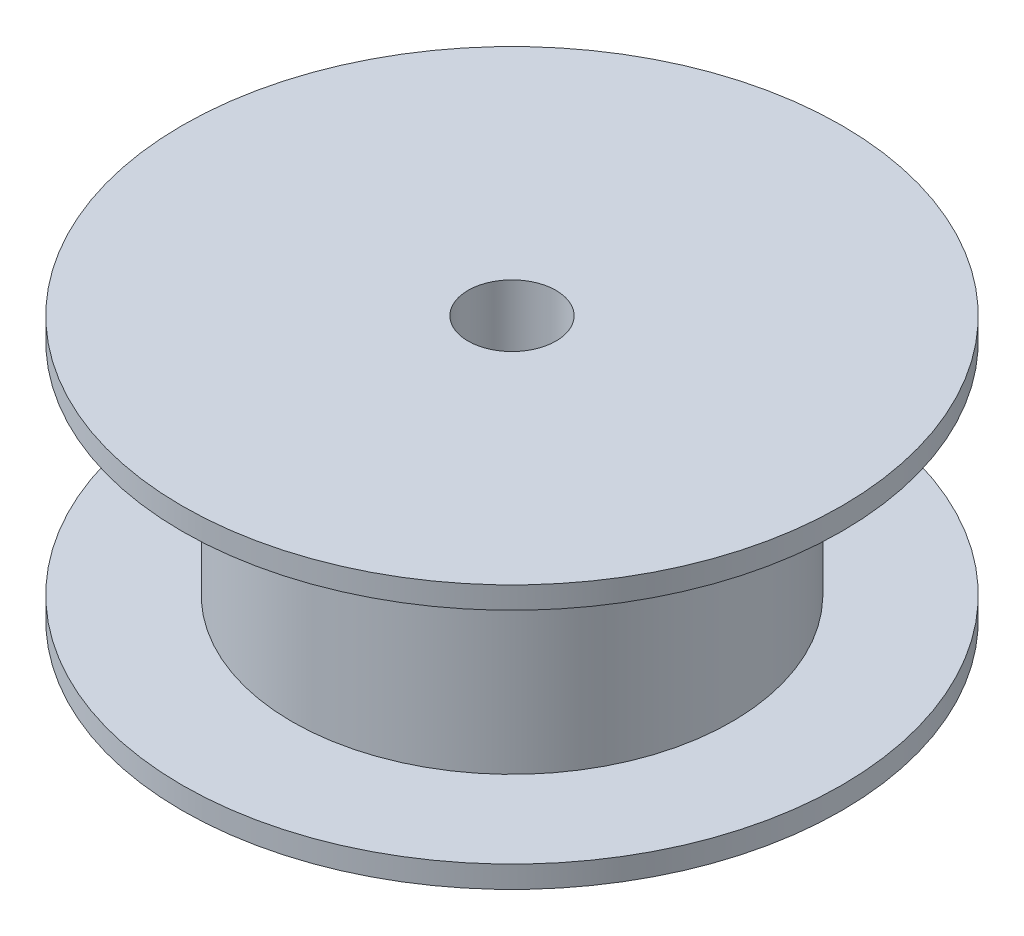
SolidWorks part; units mm, degrees
material "尼龙 6/10"
ref_plane "前视基准面" through (0, 0, 0) normal (0, 0, 1) x (1, 0, 0)
ref_plane "上视基准面" through (0, 0, 0) normal (0, 1, 0) x (1, 0, 0)
ref_plane "右视基准面" through (0, 0, 0) normal (1, 0, 0) x (0, 0, -1)
sketch "草图1" plane through (0, 0, 0) normal (0, 1, 0) x (1, 0, 0)
  circle A0 centre (0, 0) radius 10
  circle A5 centre (0, 0) radius 2
  point P14 (0, 0)
  dimension "D1" = 20
  dimension "D5" = 4
extrude "凸台-拉伸1" add sketch "草图1" along normal blind 10
sketch "草图2" plane through (0, 10, 0) normal (0, 1, 0) x (1, 0, 0)
  circle A0 centre (0, 0) radius 15
  circle A1 centre (0, 0) radius 2
  point P16 (0, 0)
  dimension "D1" = 30
  dimension "D3" = 4
extrude "凸台-拉伸2" add sketch "草图2" along normal blind 1
sketch "草图3" plane through (0, 0, 0) normal (0, -1, 0) x (1, 0, 0)
  circle A0 centre (0, 0) radius 15
  circle A1 centre (0, 0) radius 2
  point P16 (0, 0)
  dimension "D1" = 30
  dimension "D2" = 4
extrude "凸台-拉伸3" add sketch "草图3" along normal blind 1
